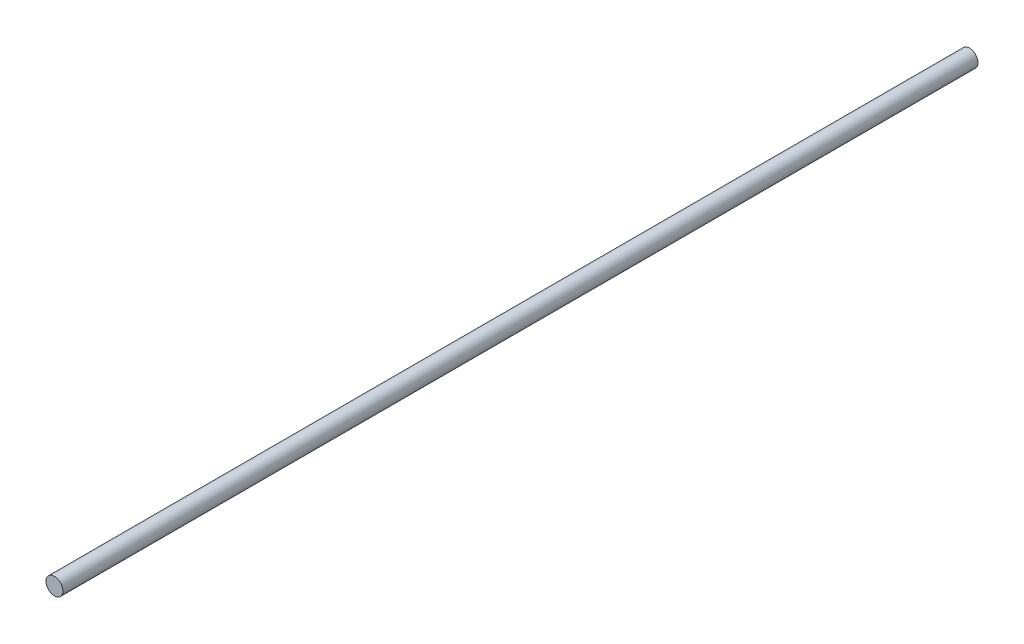
SolidWorks part; units mm, degrees
ref_plane "Front Plane" through (0, 0, 0) normal (0, 0, 1) x (1, 0, 0)
ref_plane "Top Plane" through (0, 0, 0) normal (0, 1, 0) x (1, 0, 0)
ref_plane "Right Plane" through (0, 0, 0) normal (1, 0, 0) x (0, 0, -1)
sketch "Sketch1" plane through (0, 0, 0) normal (0, 0, 1) x (1, 0, 0)
  circle A0 centre (0, 0) radius 2.5
  dimension "D1" = 5
extrude "Boss-Extrude1" add sketch "Sketch1" along normal blind 270
